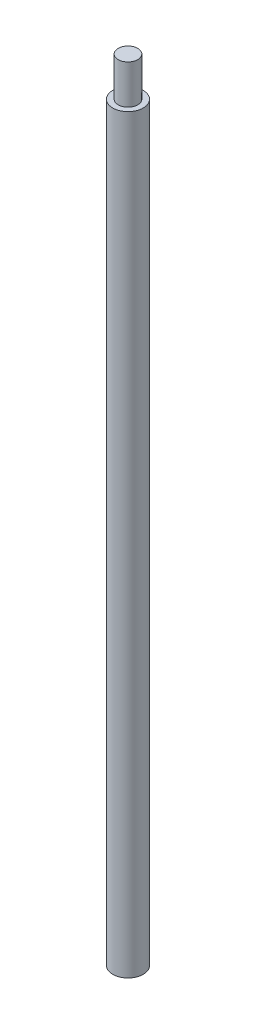
SolidWorks part; units mm, degrees
material "Plain Carbon Steel"
ref_plane "Front" through (0, 0, 0) normal (0, 0, 1) x (1, 0, 0)
ref_plane "Top" through (0, 0, 0) normal (0, 1, 0) x (1, 0, 0)
ref_plane "Right" through (0, 0, 0) normal (1, 0, 0) x (0, 0, -1)
sketch "Sketch1" plane through (0, 0, 0) normal (0, 1, 0) x (1, 0, 0)
  circle A0 centre (0, 0) radius 4.675
  dimension "D1" = 9.35
extrude "Boss-Extrude1" add sketch "Sketch1" along normal blind 230
sketch "Sketch2" plane through (0, 230, 0) normal (0, 1, 0) x (1, 0, 0)
  circle A0 centre (0, 0) radius 3
  dimension "D1" = 6
extrude "Boss-Extrude2" add sketch "Sketch2" along normal blind 12
